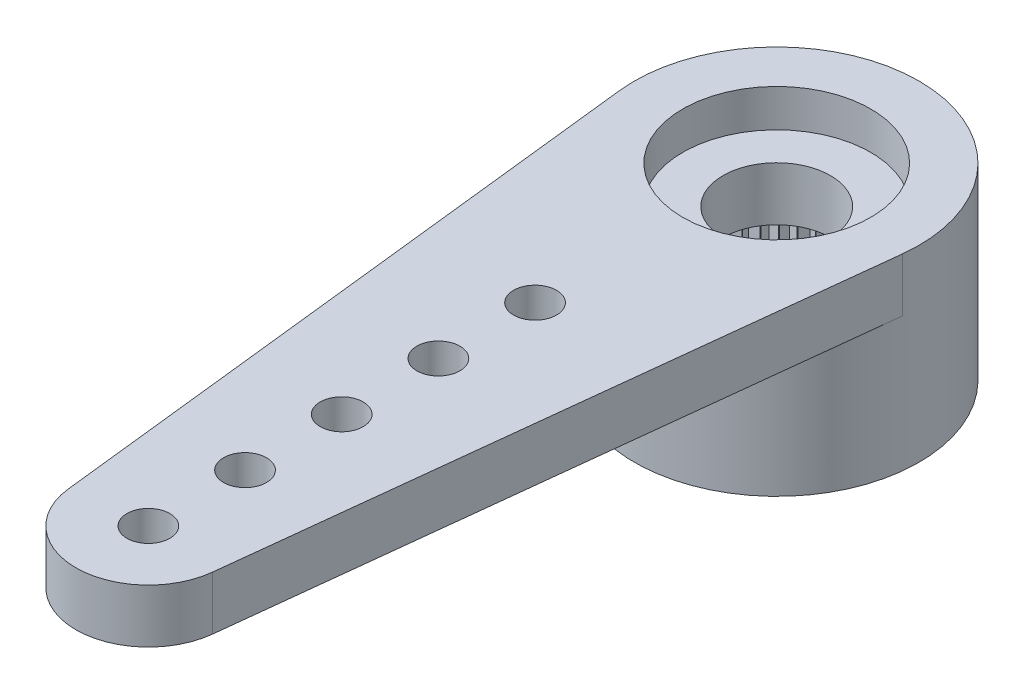
SolidWorks part; units mm, degrees
ref_plane "Front Plane" through (0, 0, 0) normal (0, 0, 1) x (1, 0, 0)
ref_plane "Top Plane" through (0, 0, 0) normal (0, 1, 0) x (1, 0, 0)
ref_plane "Right Plane" through (0, 0, 0) normal (1, 0, 0) x (0, 0, -1)
sketch "Sketch1" plane through (0, 0, 0) normal (0, 1, 0) x (1, 0, 0)
  line L0 (0, 0) -> (0, -14.859) construction
  line L1 (-1.7039, -15.0495) -> (-3.3447, -0.3739)
  line L2 (1.7039, -15.0495) -> (3.3447, -0.3739)
  arc A0 (3.3447, -0.3739) -> (-3.3447, -0.3739) centre (0, 0) ccw
  arc A1 (-1.7039, -15.0495) -> (1.7039, -15.0495) centre (0, -14.859) ccw
  dimension "D1" = 6.731
  dimension "D2" = 3.429
  dimension "D3" = 19.939
extrude "Boss-Extrude1" add sketch "Sketch1" along normal blind 1.27
sketch "Sketch2" plane through (0, 0, 0) normal (0, -1, 0) x (1, 0, 0)
  circle A0 centre (0, 0) radius 3.3655
extrude "Boss-Extrude2" add sketch "Sketch2" along normal blind 3.175
sketch "Sketch3" plane through (0, -3.175, 0) normal (0, -1, 0) x (-1, 0, 0)
  line L0 (0.3447, 2.4524) -> (0.1605, 2.2167)
  line L1 (0, 2.4765) -> (-0.1496, 2.2175)
  line L2 (0.4567, 2.1751) -> (0.3447, 2.4524)
  line L3 (0.1496, 2.2175) -> (0, 2.4765)
  line L4 (0.6826, 2.3806) -> (0.4675, 2.1728)
  line L5 (0.755, 2.0903) -> (0.6826, 2.3806)
  line L6 (1.0073, 2.2624) -> (0.7653, 2.0866)
  line L7 (1.0385, 1.9649) -> (1.0073, 2.2624)
  line L8 (1.3123, 2.1002) -> (1.0482, 1.9598)
  line L9 (1.3019, 1.8013) -> (1.3123, 2.1002)
  line L10 (1.5919, 1.8971) -> (1.3108, 1.7948)
  line L11 (1.5399, 1.6025) -> (1.5919, 1.8971)
  line L12 (1.8404, 1.6571) -> (1.5478, 1.5949)
  line L13 (1.748, 1.3726) -> (1.8404, 1.6571)
  line L14 (2.0531, 1.3848) -> (1.7547, 1.364)
  line L15 (1.922, 1.116) -> (2.0531, 1.3848)
  line L16 (2.2259, 1.0856) -> (1.9275, 1.1065)
  line L17 (2.0586, 0.8377) -> (2.2259, 1.0856)
  line L18 (2.3553, 0.7653) -> (2.0627, 0.8275)
  line L19 (2.1551, 0.543) -> (2.3553, 0.7653)
  line L20 (2.4389, 0.43) -> (2.1578, 0.5323)
  line L21 (2.2097, 0.2378) -> (2.4389, 0.43)
  line L22 (2.475, 0.0864) -> (2.2109, 0.2269)
  line L23 (2.2213, -0.0721) -> (2.475, 0.0864)
  line L24 (2.4629, -0.2589) -> (2.2209, -0.0831)
  line L25 (2.1897, -0.3805) -> (2.4629, -0.2589)
  line L26 (2.4029, -0.5991) -> (2.1878, -0.3913)
  line L27 (2.1154, -0.6816) -> (2.4029, -0.5991)
  line L28 (2.2962, -0.9277) -> (2.112, -0.692)
  line L29 (2, -0.9693) -> (2.2962, -0.9277)
  line L30 (2.1447, -1.2383) -> (1.9952, -0.9792)
  line L31 (1.8456, -1.2382) -> (2.1447, -1.2383)
  line L32 (1.9515, -1.5247) -> (1.8395, -1.2474)
  line L33 (1.6553, -1.4831) -> (1.9515, -1.5247)
  line L34 (1.7203, -1.7814) -> (1.648, -1.4912)
  line L35 (1.4328, -1.699) -> (1.7203, -1.7814)
  line L36 (1.4557, -2.0035) -> (1.4244, -1.7061)
  line L37 (1.1824, -1.8819) -> (1.4557, -2.0035)
  line L38 (1.1626, -2.1866) -> (1.1731, -1.8877)
  line L39 (0.909, -2.0281) -> (1.1626, -2.1866)
  line L40 (0.847, -2.3271) -> (0.899, -2.0326)
  line L41 (0.6179, -2.1349) -> (0.847, -2.3271)
  line L42 (0.5149, -2.4224) -> (0.6073, -2.1379)
  line L43 (0.3147, -2.2001) -> (0.5149, -2.4224)
  line L44 (0.1728, -2.4705) -> (0.3039, -2.2016)
  line L45 (-0.22, 2.0955) -> (0, 2.0955) [skipped]
  line L46 (0.0055, -2.2225) -> (0.1728, -2.4705)
  line L47 (-0.1728, -2.4705) -> (-0.0055, -2.2225)
  line L48 (-0.3039, -2.2016) -> (-0.1728, -2.4705)
  line L49 (-0.5149, -2.4224) -> (-0.3147, -2.2001)
  line L50 (-0.6073, -2.1379) -> (-0.5149, -2.4224)
  line L51 (-0.847, -2.3271) -> (-0.6179, -2.1349)
  line L52 (-0.899, -2.0326) -> (-0.847, -2.3271)
  line L53 (-1.1626, -2.1866) -> (-0.909, -2.0281)
  line L54 (-1.1731, -1.8877) -> (-1.1626, -2.1866)
  line L55 (-1.4557, -2.0035) -> (-1.1824, -1.8819)
  line L56 (-1.4244, -1.7061) -> (-1.4557, -2.0035)
  line L57 (-1.7203, -1.7814) -> (-1.4328, -1.699)
  line L58 (-1.648, -1.4912) -> (-1.7203, -1.7814)
  line L59 (-1.9515, -1.5247) -> (-1.6553, -1.4831)
  line L60 (-1.8395, -1.2474) -> (-1.9515, -1.5247)
  line L61 (-2.1447, -1.2382) -> (-1.8456, -1.2383)
  line L62 (-1.9952, -0.9792) -> (-2.1447, -1.2382)
  line L63 (-2.2962, -0.9277) -> (-2, -0.9693)
  line L64 (-2.112, -0.692) -> (-2.2962, -0.9277)
  line L65 (-2.4029, -0.5991) -> (-2.1154, -0.6816)
  line L66 (-2.1878, -0.3913) -> (-2.4029, -0.5991)
  line L67 (-2.4629, -0.2589) -> (-2.1897, -0.3805)
  line L68 (-2.2209, -0.0831) -> (-2.4629, -0.2589)
  line L69 (-2.475, 0.0864) -> (-2.2213, -0.0721)
  line L70 (-2.2109, 0.2269) -> (-2.475, 0.0864)
  line L71 (-2.4389, 0.43) -> (-2.2097, 0.2378)
  line L72 (-2.1578, 0.5323) -> (-2.4389, 0.43)
  line L73 (-2.3553, 0.7653) -> (-2.1551, 0.543)
  line L74 (-2.0627, 0.8275) -> (-2.3553, 0.7653)
  line L75 (-2.2259, 1.0856) -> (-2.0586, 0.8377)
  line L76 (-1.9275, 1.1065) -> (-2.2259, 1.0856)
  line L77 (-2.0531, 1.3848) -> (-1.922, 1.116)
  line L78 (-1.7547, 1.364) -> (-2.0531, 1.3848)
  line L79 (-1.8404, 1.6571) -> (-1.748, 1.3726)
  line L80 (-1.5478, 1.5949) -> (-1.8404, 1.6571)
  line L81 (-1.5919, 1.8971) -> (-1.5399, 1.6025)
  line L82 (-1.3108, 1.7948) -> (-1.5919, 1.8971)
  line L83 (-1.3123, 2.1002) -> (-1.3019, 1.8013)
  line L84 (-1.0482, 1.9598) -> (-1.3123, 2.1002)
  line L85 (-1.0073, 2.2624) -> (-1.0385, 1.9649)
  line L86 (-0.7653, 2.0866) -> (-1.0073, 2.2624)
  line L87 (-0.6826, 2.3806) -> (-0.755, 2.0903)
  line L88 (-0.4675, 2.1728) -> (-0.6826, 2.3806)
  line L89 (-0.3447, 2.4524) -> (-0.4567, 2.1751)
  line L90 (-0.1605, 2.2167) -> (-0.3447, 2.4524)
  arc A0 (-0.1496, 2.2175) -> (-0.1605, 2.2167) centre (0, 0) ccw
  circle A1 centre (0, 2.2225) radius 0.127 construction
  arc A2 (0.1605, 2.2167) -> (0.1496, 2.2175) centre (0, 0) ccw
  arc A3 (0.4675, 2.1728) -> (0.4567, 2.1751) centre (0, 0) ccw
  arc A4 (0.7653, 2.0866) -> (0.755, 2.0903) centre (0, 0) ccw
  arc A5 (1.0482, 1.9598) -> (1.0385, 1.9649) centre (0, 0) ccw
  arc A6 (1.3108, 1.7948) -> (1.3019, 1.8013) centre (0, 0) ccw
  arc A7 (1.5478, 1.5949) -> (1.5399, 1.6025) centre (0, 0) ccw
  arc A8 (1.7547, 1.364) -> (1.748, 1.3726) centre (0, 0) ccw
  arc A9 (1.9275, 1.1065) -> (1.922, 1.116) centre (0, 0) ccw
  arc A10 (-0.4567, 2.1751) -> (-0.4675, 2.1728) centre (0, 0) ccw
  arc A11 (-0.755, 2.0903) -> (-0.7653, 2.0866) centre (0, 0) ccw
  arc A12 (-1.0385, 1.9649) -> (-1.0482, 1.9598) centre (0, 0) ccw
  arc A13 (-1.3019, 1.8013) -> (-1.3108, 1.7948) centre (0, 0) ccw
  arc A14 (-1.5399, 1.6025) -> (-1.5478, 1.5949) centre (0, 0) ccw
  arc A15 (-1.748, 1.3726) -> (-1.7547, 1.364) centre (0, 0) ccw
  arc A16 (-1.922, 1.116) -> (-1.9275, 1.1065) centre (0, 0) ccw
  arc A17 (-2.0586, 0.8377) -> (-2.0627, 0.8275) centre (0, 0) ccw
  arc A18 (-2.1551, 0.543) -> (-2.1578, 0.5323) centre (0, 0) ccw
  arc A19 (-2.2097, 0.2378) -> (-2.2109, 0.2269) centre (0, 0) ccw
  arc A20 (-2.2213, -0.0721) -> (-2.2209, -0.0831) centre (0, 0) ccw
  arc A21 (2.0627, 0.8275) -> (2.0586, 0.8377) centre (0, 0) ccw
  arc A22 (2.1578, 0.5323) -> (2.1551, 0.543) centre (0, 0) ccw
  arc A23 (2.2109, 0.2269) -> (2.2097, 0.2378) centre (0, 0) ccw
  arc A24 (2.2209, -0.0831) -> (2.2213, -0.0721) centre (0, 0) ccw
  arc A25 (2.1878, -0.3913) -> (2.1897, -0.3805) centre (0, 0) ccw
  arc A26 (2.112, -0.692) -> (2.1154, -0.6816) centre (0, 0) ccw
  arc A27 (1.9952, -0.9792) -> (2, -0.9693) centre (0, 0) ccw
  arc A28 (1.8395, -1.2474) -> (1.8456, -1.2382) centre (0, 0) ccw
  arc A29 (1.648, -1.4912) -> (1.6553, -1.4831) centre (0, 0) ccw
  arc A30 (1.4244, -1.7061) -> (1.4328, -1.699) centre (0, 0) ccw
  arc A31 (1.1731, -1.8877) -> (1.1824, -1.8819) centre (0, 0) ccw
  arc A32 (0.899, -2.0326) -> (0.909, -2.0281) centre (0, 0) ccw
  arc A33 (0.6073, -2.1379) -> (0.6179, -2.1349) centre (0, 0) ccw
  arc A34 (0.3039, -2.2016) -> (0.3147, -2.2001) centre (0, 0) ccw
  arc A35 (-0.0055, -2.2225) -> (0.0055, -2.2225) centre (0, 0) ccw
  arc A36 (-0.3147, -2.2001) -> (-0.3039, -2.2016) centre (0, 0) ccw
  arc A37 (-0.6179, -2.1349) -> (-0.6073, -2.1379) centre (0, 0) ccw
  arc A38 (-0.909, -2.0281) -> (-0.899, -2.0326) centre (0, 0) ccw
  arc A39 (-1.1824, -1.8819) -> (-1.1731, -1.8877) centre (0, 0) ccw
  arc A40 (-1.4328, -1.699) -> (-1.4244, -1.7061) centre (0, 0) ccw
  arc A41 (-1.6553, -1.4831) -> (-1.648, -1.4912) centre (0, 0) ccw
  arc A42 (-1.8456, -1.2383) -> (-1.8395, -1.2474) centre (0, 0) ccw
  arc A43 (-2, -0.9693) -> (-1.9952, -0.9792) centre (0, 0) ccw
  arc A44 (-2.1154, -0.6816) -> (-2.112, -0.692) centre (0, 0) ccw
  arc A45 (-2.1897, -0.3805) -> (-2.1878, -0.3913) centre (0, 0) ccw
  point P145 (0, 0)
  dimension "D1" = 4.445
  dimension "D2" = 0.254
  dimension "D3" = 45
extrude "Cut-Extrude1" cut sketch "Sketch3" against normal blind 2.286
sketch "Sketch4" plane through (0, 1.27, 0) normal (0, 1, 0) x (1, 0, 0)
  circle A0 centre (0, 0) radius 2.2225
  dimension "D1" = 4.445
extrude "Cut-Extrude2" cut sketch "Sketch4" against normal blind 0.889
sketch "Sketch5" plane through (0, 0.381, 0) normal (0, 1, 0) x (1, 0, 0)
  circle A0 centre (0, 0) radius 1.27
  dimension "D1" = 2.54
extrude "Cut-Extrude3" cut sketch "Sketch5" against normal up to next
sketch "Sketch6" plane through (0, 1.27, 0) normal (0, 1, 0) x (1, 0, 0)
  line L0 (0, 0) -> (0, -14.859) construction
  circle A0 centre (0, -14.859) radius 0.508
  circle A1 centre (0, -12.573) radius 0.508
  circle A2 centre (0, -10.287) radius 0.508
  circle A3 centre (0, -8.001) radius 0.508
  circle A4 centre (0, -5.715) radius 0.508
  dimension "D1" = 1.016
  dimension "D2" = 1.016
  dimension "D3" = 1.27
  dimension "D4" = 1.27
  dimension "D5" = 1.27
  dimension "D6" = 1.27
extrude "Cut-Extrude4" cut sketch "Sketch6" against normal up to next
